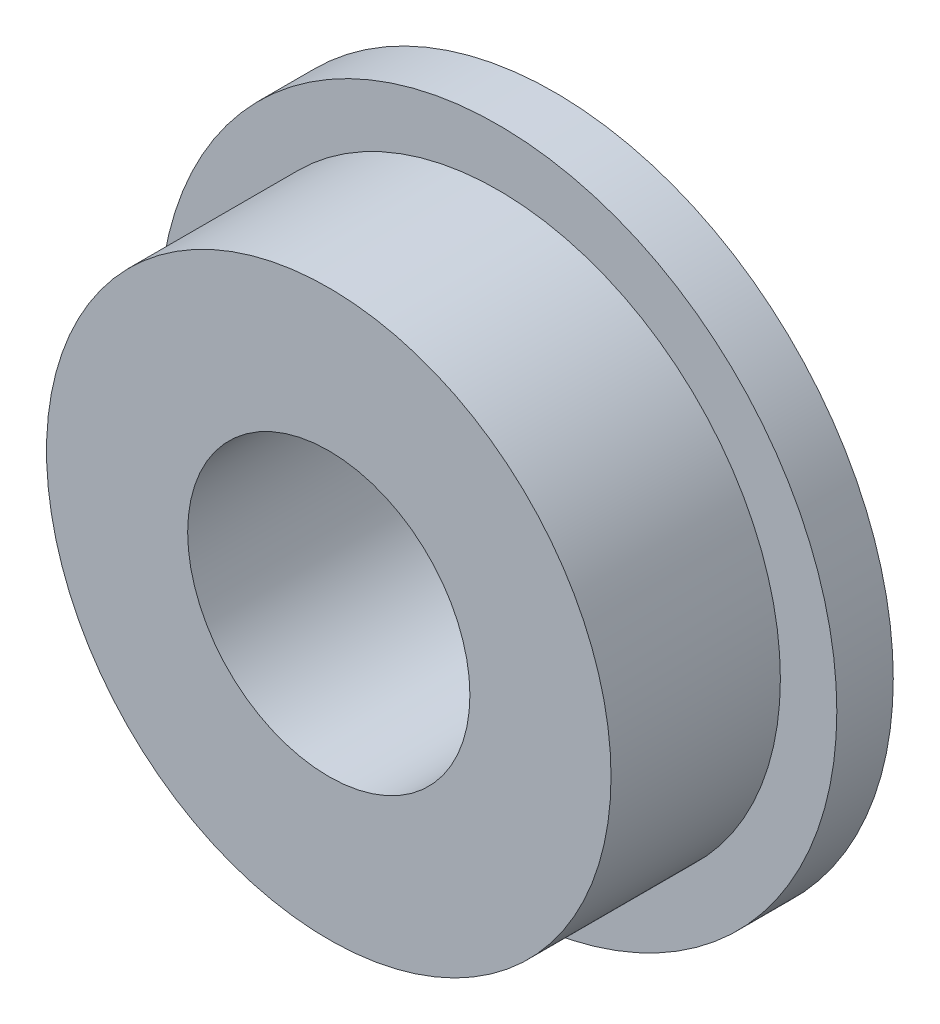
SolidWorks part; units mm, degrees
material "镀铬不锈钢"
ref_plane "前视基准面" through (0, 0, 0) normal (0, 0, 1) x (1, 0, 0)
ref_plane "上视基准面" through (0, 0, 0) normal (0, 1, 0) x (1, 0, 0)
ref_plane "右视基准面" through (0, 0, 0) normal (1, 0, 0) x (0, 0, -1)
sketch "草图1" plane through (0, 0, 0) normal (0, 0, 1) x (1, 0, 0)
  circle A0 centre (0, 0) radius 6
  dimension "D1" = 12
extrude "凸台-拉伸1" add sketch "草图1" along normal blind 1
sketch "草图2" plane through (0, 0, 1) normal (0, 0, 1) x (1, 0, 0)
  circle A0 centre (0, 0) radius 5
  dimension "D1" = 10
extrude "凸台-拉伸2" add sketch "草图2" along normal blind 3
sketch "草图3" plane through (0, 0, 4) normal (0, 0, 1) x (1, 0, 0)
  circle A0 centre (0, 0) radius 2.5
  dimension "D1" = 5
extrude "切除-拉伸1" cut sketch "草图3" against normal blind 7
